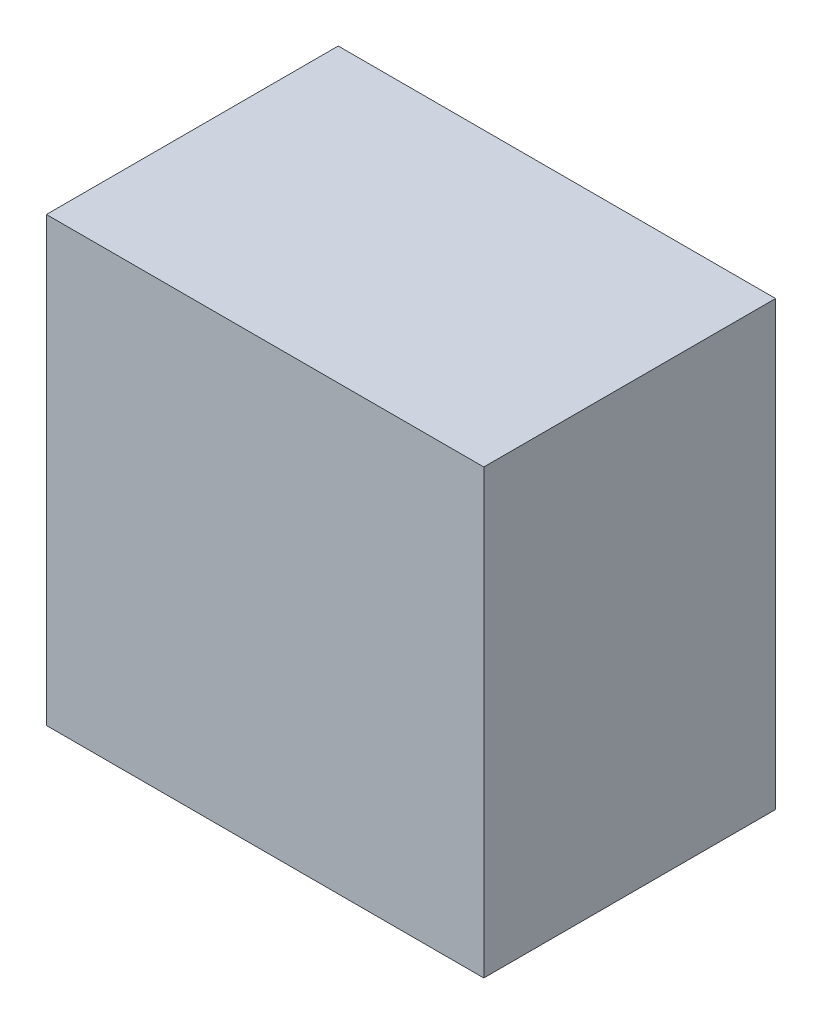
SolidWorks part; units mm, degrees
ref_plane "Front Plane" through (0, 0, 0) normal (0, 0, 1) x (1, 0, 0)
ref_plane "Top Plane" through (0, 0, 0) normal (0, 1, 0) x (1, 0, 0)
ref_plane "Right Plane" through (0, 0, 0) normal (1, 0, 0) x (0, 0, -1)
other "Configuration Table"
sketch "Sketch1" plane through (0, 0, 0) normal (0, 0, 1) x (1, 0, 0)
  line L1 (-45.5931, 23.5799) -> (29.3481, 23.5799)
  line L2 (-45.5931, 23.5799) -> (-45.5931, -52.2511)
  line L3 (-45.5931, -52.2511) -> (29.3481, -52.2511)
  line L4 (29.3481, 23.5799) -> (29.3481, -52.2511)
extrude "Boss-Extrude1" add sketch "Sketch1" along normal blind 50
sketch "Sketch2" plane through (0, 0, 50) normal (0, 0, 1) x (1, 0, 0)
  circle A0 centre (11.2129, -33.4455) radius 11.3713
sketch "Sketch3" plane through (29.3481, 0, 0) normal (1, 0, 0) x (0, 0, -1)
  line L0 (-50, -52.2511) -> (-50, 23.5799) construction
  line L1 (0, -52.2511) -> (0, 23.5799) construction
  spline S0 degree 2 poles (-50, -30.7191) (-21.2728, -1.7709) (0, -39.2363) knots 0 0 0 1 1 1
ref_plane "Plane1" through (0, 0, 25.3102) normal (0, 0, 1) x (1, 0, 0)
sketch "Sketch4" plane through (0, 0, 25.3102) normal (0, 0, 1) x (1, 0, 0)
  circle A0 centre (29.3481, -18.1303) radius 10.9629
